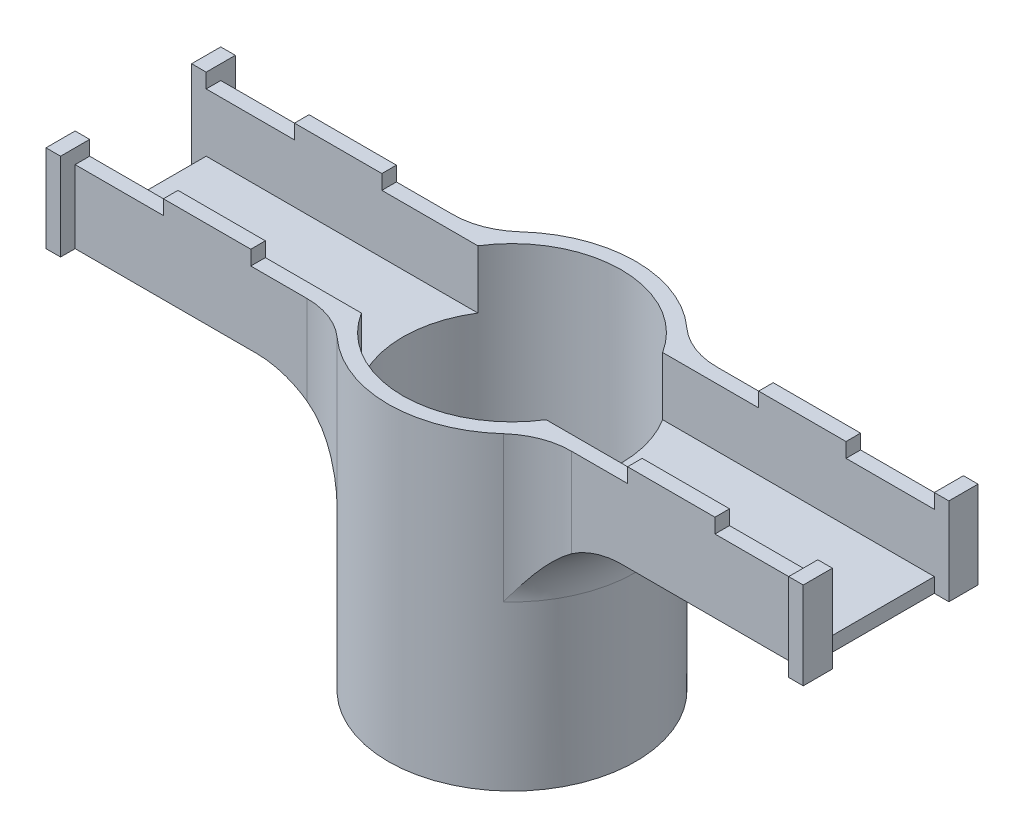
SolidWorks part; units mm, degrees
ref_plane "前视基准面" through (0, 0, 0) normal (0, 0, 1) x (1, 0, 0)
ref_plane "上视基准面" through (0, 0, 0) normal (0, 1, 0) x (1, 0, 0)
ref_plane "右视基准面" through (0, 0, 0) normal (1, 0, 0) x (0, 0, -1)
sketch "草图1" plane through (0, 0, 0) normal (0, 1, 0) x (1, 0, 0)
  line L0 (-22.0878, 0) -> (22.0878, 0) construction
  line L1 (6.7175, 6.7175) -> (0, 0) construction
  circle A0 centre (0, 0) radius 17
  circle A1 centre (0, 0) radius 7
  circle A2 centre (0, 0) radius 9.5 construction
  circle A3 centre (6.7175, 6.7175) radius 1.6
  circle A4 centre (2.4588, -9.1763) radius 1.6
  circle A5 centre (-9.1763, 2.4588) radius 1.6
  point P9 (0, 0)
  point P17 (0, 0)
  dimension "D1" = 34
  dimension "D2" = 14
  dimension "D3" = 19
  dimension "D4" = 3.2
  dimension "D5" = 45
  dimension "D6" = 3
extrude "凸台-拉伸1" add sketch "草图1" against normal blind 2
sketch "草图2" plane through (0, 0, 0) normal (0, 1, 0) x (1, 0, 0)
  circle A2 centre (0, 0) radius 15
  circle A3 centre (0, 0) radius 17
  dimension "D1" = 30
  dimension "D2" = 2
extrude "凸台-拉伸2" add sketch "草图2" along normal blind 40.5
ref_plane "基准面1" through (50, 0, 0) normal (1, 0, 0) x (0, 0, -1)
sketch "草图4" plane through (50, 0, 0) normal (1, 0, 0) x (0, 0, -1)
  line L0 (-10, 40.5) -> (-8, 40.5)
  line L1 (-8, 40.5) -> (-8, 32.5)
  line L2 (-8, 32.5) -> (8, 32.5)
  line L3 (8, 32.5) -> (8, 40.5)
  line L4 (8, 40.5) -> (10, 40.5)
  line L5 (10, 40.5) -> (10, 30.5)
  line L6 (10, 30.5) -> (-10, 30.5)
  line L7 (-10, 30.5) -> (-10, 40.5)
  line L8 (0, 17.6029) -> (0, 47.2393) construction
  line L10 (17, 40.5) -> (-17, 40.5) construction
  point P11 (0, 32.5)
  dimension "D1" = 2
  dimension "D2" = 2
  dimension "D4" = 16
  dimension "D5" = 8
  dimension "D3" = 2
extrude "凸台-拉伸3" add sketch "草图4" against normal up to next
sketch "草图5" plane through (50, 0, 0) normal (1, 0, 0) x (0, 0, -1)
  line L0 (-10, 30.5) -> (10, 30.5) construction
  line L1 (-8, 42.5) -> (-12, 42.5)
  line L2 (-8, 42.5) -> (-8, 30.5)
  line L3 (-8, 30.5) -> (-12, 30.5)
  line L4 (-12, 42.5) -> (-12, 30.5)
  line L5 (-10, 30.5) -> (10, 30.5) construction
  line L6 (8, 42.5) -> (12, 42.5)
  line L7 (8, 42.5) -> (8, 30.5)
  line L8 (8, 30.5) -> (12, 30.5)
  line L9 (12, 42.5) -> (12, 30.5)
  line L10 (-8, 32.5) -> (-8, 40.5) construction
  line L11 (-8, 40.5) -> (-10, 40.5) construction
  line L12 (8, 40.5) -> (8, 32.5) construction
  line L13 (10, 40.5) -> (8, 40.5) construction
  dimension "D1" = 4
  dimension "D2" = 4
  dimension "D3" = 2
  dimension "D4" = 2
extrude "凸台-拉伸4" add sketch "草图5" along normal blind 2
sketch "草图6" plane through (50, 0, 0) normal (1, 0, 0) x (0, 0, -1)
  line L1 (-8, 40.5) -> (8, 40.5)
  line L2 (-8, 40.5) -> (-8, 32.5)
  line L3 (-8, 32.5) -> (8, 32.5)
  line L4 (8, 40.5) -> (8, 32.5)
extrude "切除-拉伸1" cut sketch "草图6" against normal up to next
sketch "草图7" plane through (0, 40.5, 0) normal (0, 1, 0) x (1, 0, 0)
  line L0 (12.6886, -8) -> (50, -8) construction
  line L1 (25.8739, -8) -> (37.8739, -8)
  line L2 (25.8739, -8) -> (25.8739, -10)
  line L3 (25.8739, -10) -> (37.8739, -10)
  line L4 (37.8739, -8) -> (37.8739, -10)
  line L5 (13.7477, -10) -> (50, -10) construction
  line L6 (31.8739, -10) -> (31.8739, -1.2949) construction
  point P13 (31.8739, -10)
  dimension "D1" = 12
extrude "凸台-拉伸5" add sketch "草图7" along normal blind 2
mirror "镜向1" about plane through (0, 0, 0) normal (0, 0, 1) of "凸台-拉伸5"
mirror "镜向2" about plane through (0, 0, 0) normal (1, 0, 0) of "镜向1", "切除-拉伸1", "凸台-拉伸4", "凸台-拉伸3"
fillet "圆角1" radius 10 6 edges at (-17, 30.5, 0) (17, 30.5, 0) (-13.7477, 35.5, -10) (13.7477, 35.5, -10) (-13.7477, 35.5, 10) (13.7477, 35.5, 10)
equation "\"拨盘中径\"= 64'8ball"
equation "\"球通道直径\"= 18"
equation "\"壁厚\"=2"
equation "\"加强筋高\"= 4"
equation "\"M3螺丝孔\"= 3.2"
equation "\"M3沉头孔\"= 6.5'杯头螺钉头高3mm"
equation "\"M3螺母孔\"= 6"
equation "\"电机杯直径\"= 30"
equation "\"D1@草图1\"=\"电机杯直径\"+\"壁厚\"*2"
equation "\"D4@草图1\"=\"M3螺丝孔\""
equation "\"D1@凸台-拉伸1\"=\"壁厚\""
equation "\"D1@草图2\"=\"电机杯直径\""
equation "\"D2@草图2\"=\"壁厚\""
equation "\"线槽宽\"= 16"
equation "\"线槽高\"= 8"
equation "\"D1@草图4\"=\"壁厚\""
equation "\"D2@草图4\"=\"壁厚\""
equation "\"D4@草图4\"=\"线槽宽\""
equation "\"D5@草图4\"=\"线槽高\""
equation "\"D3@草图4\"=\"壁厚\""
equation "\"D1@草图5\"=\"壁厚\"*2"
equation "\"D2@草图5\"= \"壁厚\" *2"
equation "\"D1@凸台-拉伸4\"=\"壁厚\""
equation "\"D1@凸台-拉伸5\"=\"壁厚\""
equation "\"D3@草图5\"=\"壁厚\""
equation "\"D4@草图5\"=\"壁厚\""
equation "\"电机尺寸1\"= 36.5'安装面到出线口的距离"
equation "\"D1@凸台-拉伸2\"=\"电机尺寸1\"+ \"线槽高\"/2"
